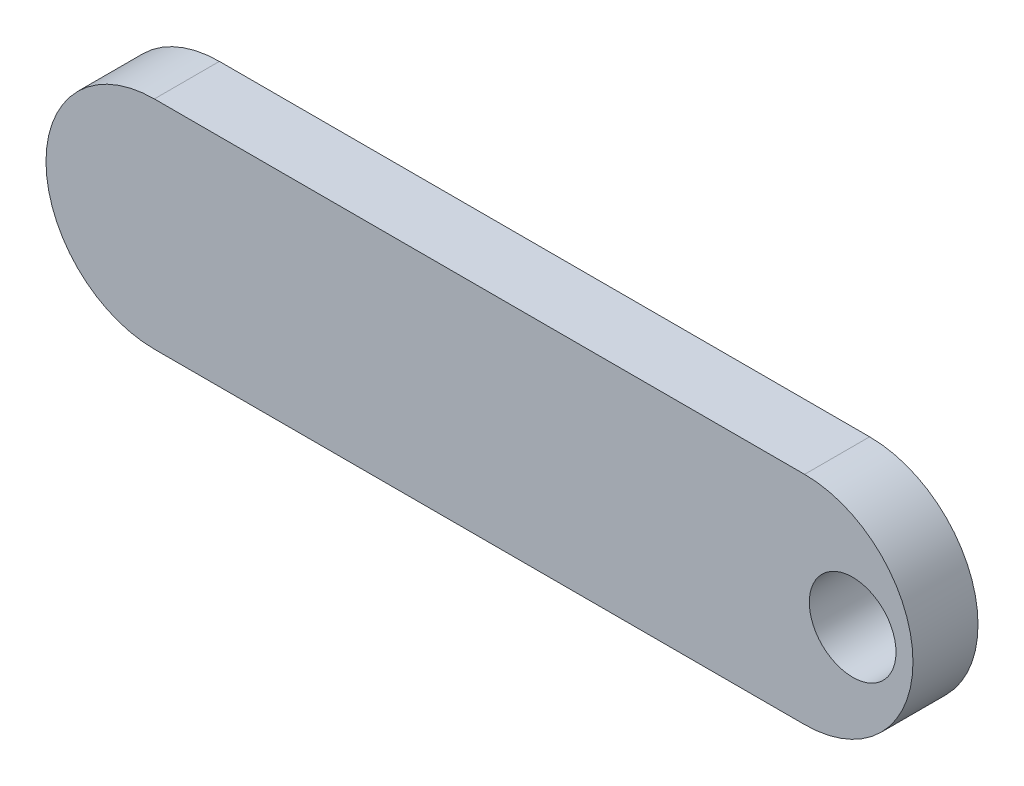
SolidWorks part; units mm, degrees
ref_plane "Plan de face" through (0, 0, 0) normal (0, 0, 1) x (1, 0, 0)
ref_plane "Plan de dessus" through (0, 0, 0) normal (0, 1, 0) x (1, 0, 0)
ref_plane "Plan de droite" through (0, 0, 0) normal (1, 0, 0) x (0, 0, -1)
sketch "Esquisse1" plane through (0, 0, 0) normal (0, 0, 1) x (1, 0, 0)
  line L0 (0, 0) -> (30, 0) construction
  line L1 (0, 5) -> (30, 5)
  line L2 (0, -5) -> (30, -5)
  arc A0 (0, 5) -> (0, -5) centre (0, 0) ccw
  arc A1 (30, -5) -> (30, 5) centre (30, 0) ccw
  point P3 (15, 0)
  dimension "D2" = 5
  dimension "D1" = 30
extrude "Boss.-Extru.1" add sketch "Esquisse1" along normal blind 3
sketch "Esquisse2" plane through (0, 0, 3) normal (0, 0, 1) x (1, 0, 0)
  line L1 (30, 5) -> (0, 5) construction
  circle A2 centre (32.2173, 0) radius 2
  dimension "D1" = 4
  dimension "D2" = 5
extrude "Enlèv. mat.-Extru.1" cut sketch "Esquisse2" against normal blind 3
